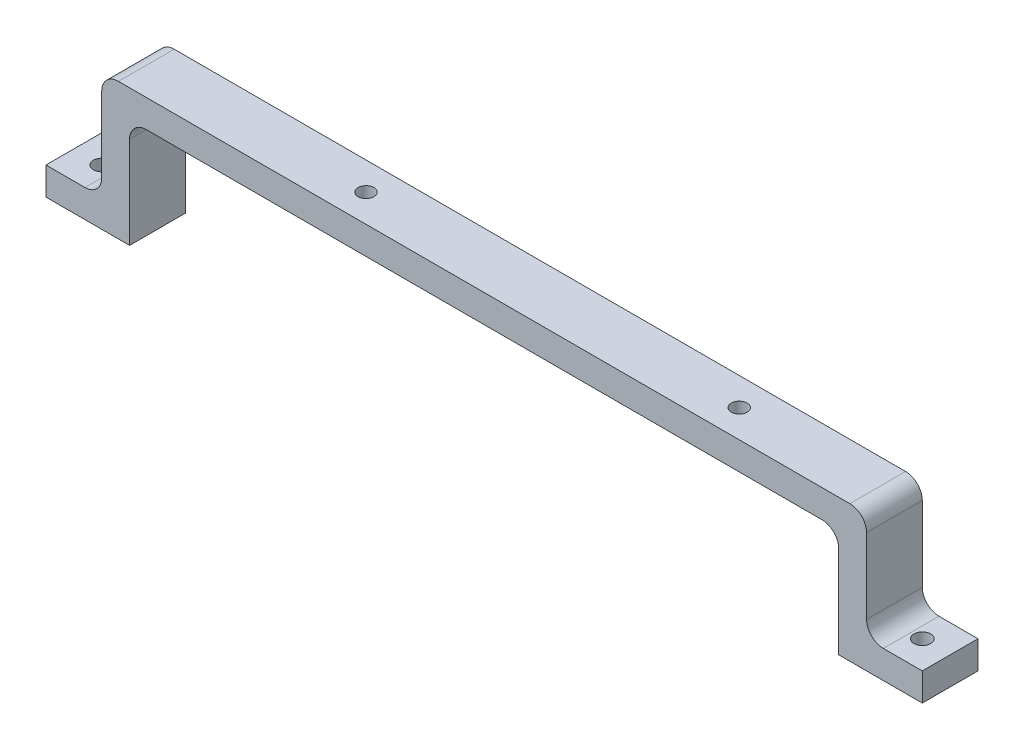
SolidWorks part; units mm, degrees
ref_plane "Front Plane" through (0, 0, 0) normal (0, 0, 1) x (1, 0, 0)
ref_plane "Top Plane" through (0, 0, 0) normal (0, 1, 0) x (1, 0, 0)
ref_plane "Right Plane" through (0, 0, 0) normal (1, 0, 0) x (0, 0, -1)
sketch "Sketch1" plane through (0, 0, 0) normal (0, 0, 1) x (1, 0, 0)
  line L0 (0, 0) -> (-68.64, 0)
  line L1 (-68.64, 0) -> (-68.64, -19.5)
  line L2 (-68.64, -19.5) -> (-78.64, -19.5)
  line L3 (-78.64, -19.5) -> (-78.64, -24.5)
  line L4 (-78.64, -24.5) -> (-63.64, -24.5)
  line L5 (-63.64, -24.5) -> (-63.64, -5)
  line L6 (-63.64, -5) -> (0, -5)
  line L7 (0, -5) -> (0, 0)
  line L8 (0, -5) -> (0, -46.6012) construction
  dimension "D1" = 5
  dimension "D2" = 5
  dimension "D3" = 5
  dimension "D4" = 63.64
  dimension "D5" = 19.5
  dimension "D6" = 15
extrude "Boss-Extrude1" add sketch "Sketch1" along normal blind 10
sketch "Sketch2" plane through (0, -19.5, 0) normal (0, 1, 0) x (1, 0, 0)
  line L0 (-73.64, 0) -> (-73.64, -10) construction
  line L1 (-68.64, 0) -> (-78.64, 0) construction
  line L2 (-68.64, -10) -> (-78.64, -10) construction
  line L3 (-78.64, -5) -> (-68.64, -5) construction
  line L4 (-78.64, -10) -> (-78.64, 0) construction
  line L5 (-68.64, -10) -> (-68.64, 0) construction
  circle A0 centre (-73.64, -5) radius 1.5
  dimension "D1" = 3
extrude "Cut-Extrude1" cut sketch "Sketch2" against normal blind 10
fillet "Fillet1" radius 3 3 edges at (-63.64, -5, 5) (-68.64, 0, 5) (-68.64, -19.5, 5)
mirror "Mirror1" about plane through (0, -5, 10) normal (-1, 0, 0) of "Fillet1", "Cut-Extrude1", "Boss-Extrude1"
sketch "Sketch3" plane through (0, 0, 0) normal (0, 1, 0) x (1, 0, 0)
  circle A0 centre (40.7886, -5) radius 1.425
  circle A1 centre (-26.2114, -5) radius 1.425
extrude "Cut-Extrude2" cut sketch "Sketch3" against normal blind 10
